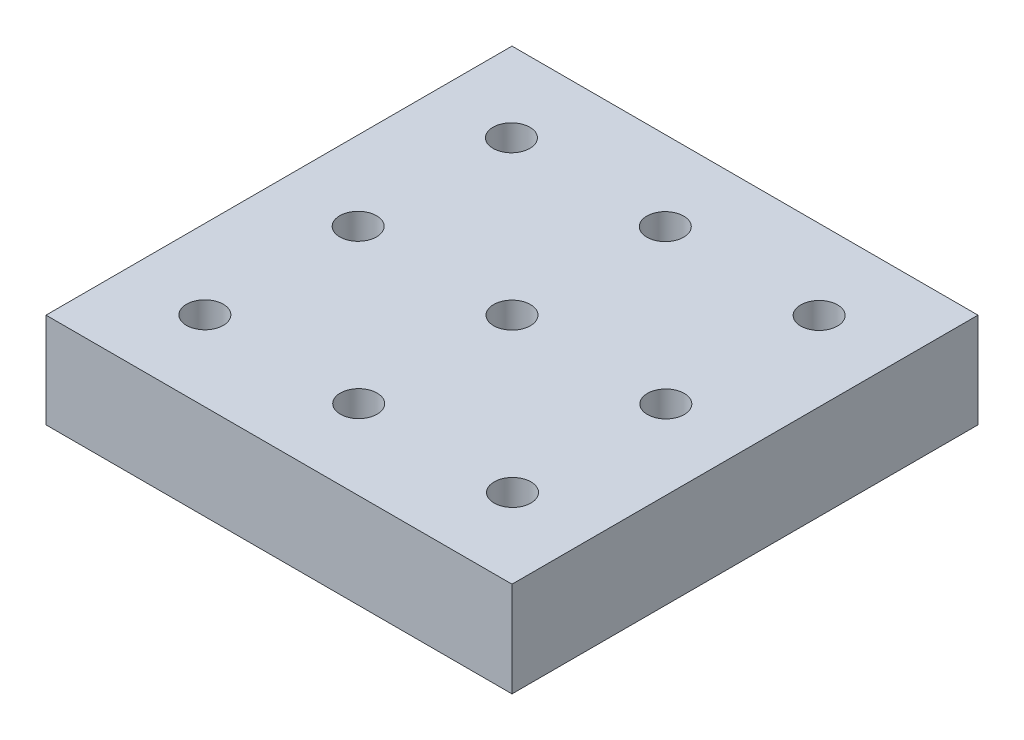
SolidWorks part; units mm, degrees
ref_plane "Front Plane" through (0, 0, 0) normal (0, 0, 1) x (1, 0, 0)
ref_plane "Top Plane" through (0, 0, 0) normal (0, 1, 0) x (1, 0, 0)
ref_plane "Right Plane" through (0, 0, 0) normal (1, 0, 0) x (0, 0, -1)
sketch "Sketch1" plane through (0, 0, 0) normal (0, 1, 0) x (1, 0, 0)
  line L1 (-121.8597, 43.7102) -> (-121.8597, 119.7102)
  line L2 (-121.8597, 119.7102) -> (-197.8597, 119.7102)
  line L3 (-197.8597, 119.7102) -> (-197.8597, 43.7102)
  line L4 (-197.8597, 43.7102) -> (-121.8597, 43.7102)
  circle A0 centre (-159.8597, 81.7102) radius 3
  circle A1 centre (-134.7695, 81.7102) radius 3
  circle A2 centre (-184.9499, 81.7102) radius 3
  circle A3 centre (-184.9499, 106.7102) radius 3
  circle A4 centre (-159.8597, 106.7102) radius 3
  circle A5 centre (-134.7695, 106.7102) radius 3
  circle A6 centre (-134.7695, 56.7102) radius 3
  circle A7 centre (-159.8597, 56.7102) radius 3
  circle A8 centre (-184.9499, 56.7102) radius 3
extrude "Boss-Extrude1" add sketch "Sketch1" along normal blind 15.5
